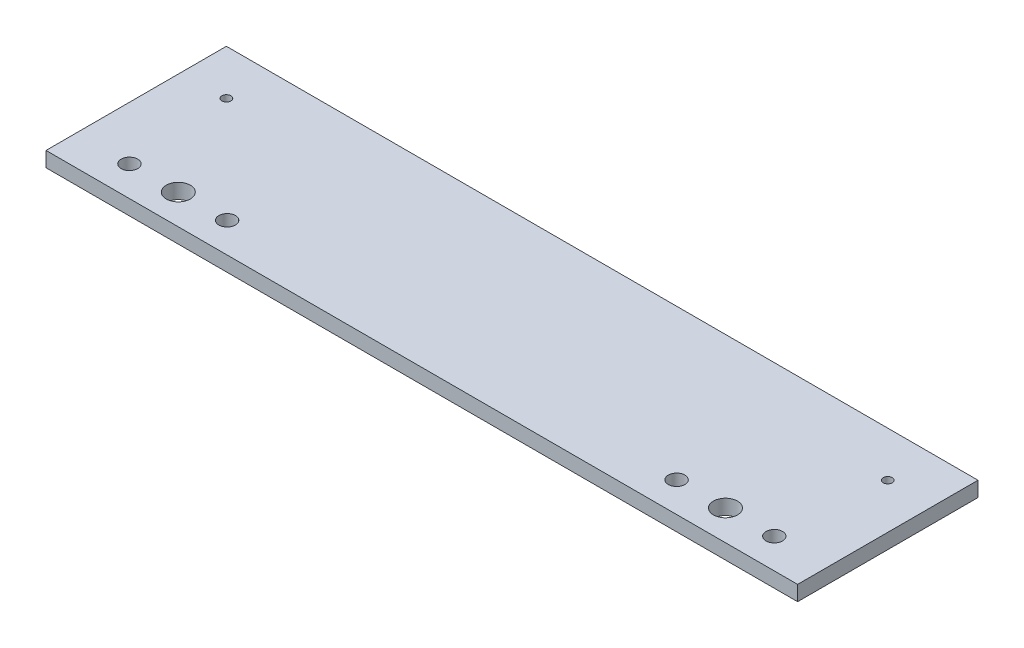
SolidWorks part; units mm, degrees
ref_plane "Front Plane" through (0, 0, 0) normal (0, 0, 1) x (1, 0, 0)
ref_plane "Top Plane" through (0, 0, 0) normal (0, 1, 0) x (1, 0, 0)
ref_plane "Right Plane" through (0, 0, 0) normal (1, 0, 0) x (0, 0, -1)
sketch "Sketch1" plane through (0, 0, 0) normal (0, 1, 0) x (1, 0, 0)
  line L0 (0, 0) -> (0, 64.2675) construction
  line L1 (-125, -45) -> (125, -45)
  line L2 (-125, -45) -> (-125, 15)
  line L3 (-125, 15) -> (125, 15)
  line L4 (125, -45) -> (125, 15)
  circle A0 centre (-91, -35) radius 4
  circle A1 centre (91, -35) radius 4
  point P0 (0, 0)
  dimension "D6" = 8
  dimension "D1" = 250
  dimension "D2" = 60
  dimension "D3" = 91
  dimension "D4" = 125
  dimension "D5" = 10
extrude "Boss-Extrude1" add sketch "Sketch1" along normal blind 5
sketch "Sketch2" plane through (0, 0, 0) normal (0, -1, 0) x (1, 0, 0)
  circle A0 centre (110, 0) radius 1.5
  circle A1 centre (74.75, 35) radius 2.75
  circle A2 centre (107.25, 35) radius 2.75
  circle A3 centre (-110, 0) radius 1.5
  circle A4 centre (-74.75, 35) radius 2.75
  circle A5 centre (-107.25, 35) radius 2.75
extrude "Cut-Extrude1" cut sketch "Sketch2" against normal blind 10
